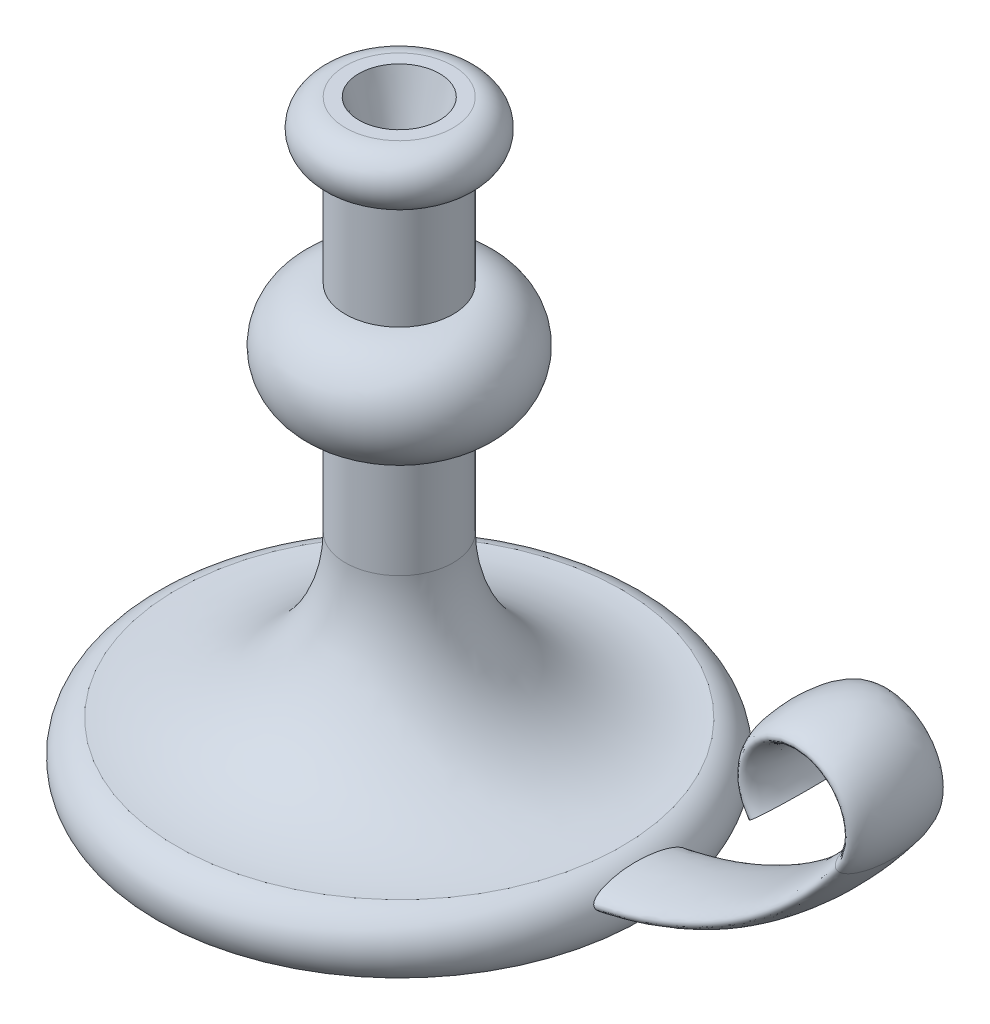
SolidWorks part; units mm, degrees
ref_plane "Płaszczyzna przednia" through (0, 0, 0) normal (0, 0, 1) x (1, 0, 0)
ref_plane "Płaszczyzna górna" through (0, 0, 0) normal (0, 1, 0) x (1, 0, 0)
ref_plane "Płaszczyzna prawa" through (0, 0, 0) normal (1, 0, 0) x (0, 0, -1)
sketch "Szkic1" plane through (0, 0, 0) normal (0, 0, 1) x (1, 0, 0)
  line L0 (0, 0) -> (0, 220)
  line L1 (0, 220) -> (20, 220)
  line L2 (20, 200) -> (20, 160)
  line L3 (20, 120) -> (20, 80)
  line L4 (90, 0) -> (0, 0)
  arc A0 (20, 220) -> (20, 200) centre (20, 210) cw
  arc A1 (20, 160) -> (20, 120) centre (20, 140) cw
  arc A2 (20, 80) -> (82.6918, 20.0604) centre (80, 80) ccw
  arc A4 (82.6918, 20.0604) -> (90, 0) centre (80.2355, 7.8041) cw
  dimension "D3" = 10
  dimension "D5" = 20
  dimension "D7" = 60
  dimension "D8" = 12.5
  dimension "D1" = 220
  dimension "D2" = 20
  dimension "D4" = 40
  dimension "D6" = 80
  dimension "D9" = 90
revolve "Obrót1" add sketch "Szkic1" angle 360 about L0
sketch "Szkic2" plane through (0, 0, 0) normal (0, 0, 1) x (1, 0, 0)
  line L0 (0, 10) -> (60, 10)
  arc A0 (60, 10) -> (180, 70) centre (60, 160) ccw
  arc A1 (180, 70) -> (148, 70) centre (164, 82) ccw
  point P6 (0, 0)
  point P7 (14.1194, 10.8995)
  point P8 (0, 9.6736)
  dimension "D2" = 150
  dimension "D4" = 20
  dimension "D1" = 60
  dimension "D3" = 60
  dimension "D5" = 10
sketch "Szkic3" plane through (0, 0, 0) normal (1, 0, 0) x (0, 0, -1)
  ellipse E0 centre (0, 10) end of major axis (17.5, 10) minor radius 5
  point P1 (0, 0)
  dimension "D1" = 35
  dimension "D2" = 10
sweep "Wyciągnięcie po ścieżce1" add profiles "Szkic3" path "Szkic2"
sketch "Szkic4" plane through (0, 220, 0) normal (0, 1, 0) x (1, 0, 0)
  circle A0 centre (0, 0) radius 15
  dimension "D1" = 30
extrude "Wytnij-wyciągnięcie1" cut sketch "Szkic4" against normal blind 25 draft 15
